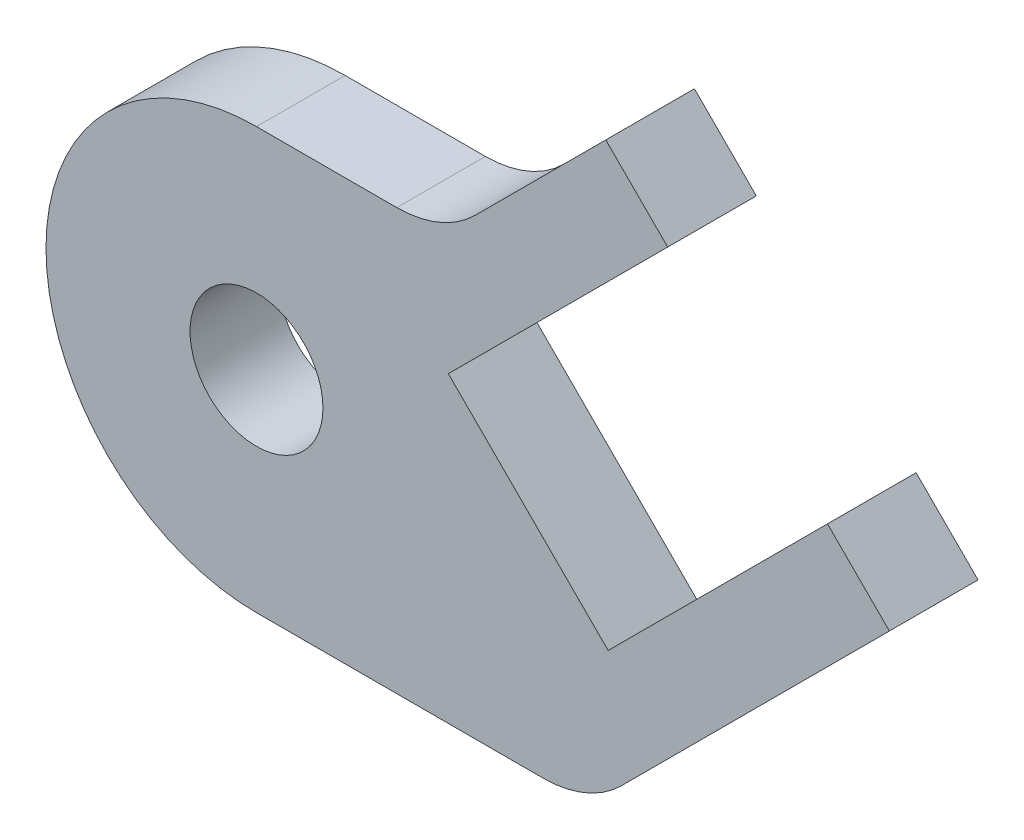
SolidWorks part; units mm, degrees
material "Foam"
ref_plane "Front Plane" through (0, 0, 0) normal (0, 0, 1) x (1, 0, 0)
ref_plane "Top Plane" through (0, 0, 0) normal (0, 1, 0) x (1, 0, 0)
ref_plane "Right Plane" through (0, 0, 0) normal (1, 0, 0) x (0, 0, -1)
sketch "Sketch1" plane through (0, 0, 0) normal (0, 0, 1) x (1, 0, 0)
  line L0 (51.4027, 28) -> (24.5327, 1.1299) construction
  line L1 (0, -19) -> (30, -19)
  line L2 (17.3202, 8.3424) -> (31.7452, -6.0825)
  line L3 (31.7452, -6.0825) -> (58.6152, 20.7875)
  line L4 (17.3202, 8.3424) -> (44.1902, 35.2125)
  line L5 (30, -19) -> (64.2014, 15.2014)
  line L6 (44.1902, 35.2125) -> (58.6152, 20.7875) construction
  line L7 (64.2014, 15.2014) -> (58.6152, 20.7875)
  line L8 (0, 0) -> (0, 28) construction
  line L9 (44.1902, 35.2125) -> (38.6041, 40.7986)
  line L10 (38.6041, 40.7986) -> (16.8055, 19)
  line L11 (16.8055, 19) -> (0, 19)
  line L12 (0, 0) -> (-19, 0) construction
  line L13 (51.4027, 28) -> (0, 28) construction
  arc A0 (0, 19) -> (0, -19) centre (0, 0) ccw
  circle A1 centre (0, 0) radius 2.5
  dimension "D5" = 5
  dimension "D4" = 36.2
  dimension "D8" = 30
  dimension "D7" = 28
  dimension "D1" = 38
  dimension "D2" = 20.4
  dimension "D3" = 38
  dimension "D6" = 45
extrude "Boss-Extrude1" add sketch "Sketch1" along normal blind 8
sketch "Sketch2" plane through (0, 0, 8) normal (0, 0, 1) x (1, 0, 0)
  line L0 (44.1902, 35.2125) -> (38.6041, 40.7986) construction
  line L1 (44.1902, 35.2125) -> (58.6152, 20.7875) construction
  line L3 (24.5327, 1.1299) -> (51.4027, 28) construction
  line L4 (31.7452, -6.0825) -> (17.3202, 8.3424) construction
  circle A0 centre (38.8781, 35.5749) radius 1.5
  circle A1 centre (58.9776, 15.4754) radius 1.5
  dimension "D1" = 3
  dimension "D2" = 3.5
  dimension "D3" = 28.425
extrude "Cut-Extrude1" cut sketch "Sketch2" against normal through all
fillet "Fillet1" radius 10 2 edges at (16.8055, 19, 4) (30, -19, 4)
sketch "Sketch3" plane through (0, 0, 8) normal (0, 0, 1) x (1, 0, 0)
  line L0 (38.6041, 40.7986) -> (64.2014, 15.2014)
  line L1 (64.2014, 15.2014) -> (57.1303, 8.1303)
  line L2 (32.9289, -16.0711) -> (64.2014, 15.2014) construction
  line L3 (57.1303, 8.1303) -> (31.533, 33.7276)
  line L4 (38.6041, 40.7986) -> (19.7344, 21.9289) construction
  line L5 (31.533, 33.7276) -> (38.6041, 40.7986)
  circle A0 centre (0, 0) radius 6
  dimension "D2" = 12
  dimension "D1" = 10
extrude "Cut-Extrude2" cut sketch "Sketch3" against normal through all
equation "\"D2@Sketch1\"=20.20mm+\"cut_free@Parameters@Parameters.SLDPRT\""
